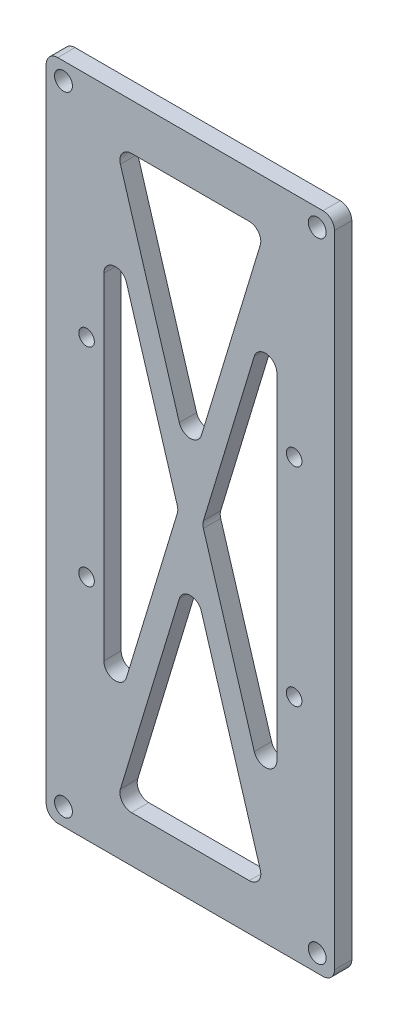
SolidWorks part; units mm, degrees
material "环氧玻璃布层压板"
ref_plane "前视基准面" through (0, 0, 0) normal (0, 0, 1) x (1, 0, 0)
ref_plane "上视基准面" through (0, 0, 0) normal (0, 1, 0) x (1, 0, 0)
ref_plane "右视基准面" through (0, 0, 0) normal (1, 0, 0) x (0, 0, -1)
sketch "草图1" plane through (0, 0, 0) normal (0, 0, 1) x (1, 0, 0)
  line L0 (25, -25) -> (25, 25)
  line L1 (-18, -18) -> (18, -18) construction
  line L2 (-18, -18) -> (-18, 18) construction
  line L3 (-18, 18) -> (18, 18) construction
  line L4 (18, -18) -> (18, 18) construction
  line L5 (0, 18) -> (0, -18) construction
  line L6 (-18, 0) -> (18, 0) construction
  line L7 (-25, 25) -> (25, 25)
  line L8 (-25, -25) -> (-25, 25)
  line L9 (-25, -25) -> (25, -25)
  circle A0 centre (18, 18) radius 1.35
  circle A1 centre (-18, 18) radius 1.35
  circle A2 centre (-18, -18) radius 1.35
  circle A3 centre (18, -18) radius 1.35
  point P0 (0, 0)
  dimension "D3" = 7
  dimension "D4" = 2.7
  dimension "D1" = 36
  dimension "D2" = 36
extrude "凸台-拉伸1" add sketch "草图1" along normal blind 3
sketch "草图2" plane through (0, 0, 3) normal (0, 0, 1) x (1, 0, 0)
  line L1 (-25, -57.5) -> (25, -57.5)
  line L2 (-25, -57.5) -> (-25, 57.5)
  line L3 (-25, 57.5) -> (25, 57.5)
  line L4 (25, -57.5) -> (25, 57.5)
  line L5 (0, 57.5) -> (0, -57.5) construction
  line L6 (-25, 0) -> (25, 0) construction
  line L8 (25, -25) -> (25, 25) construction
  line L9 (-22, -54.5) -> (22, -54.5) construction
  line L10 (-22, -54.5) -> (-22, 54.5) construction
  line L11 (-22, 54.5) -> (22, 54.5) construction
  line L12 (22, -54.5) -> (22, 54.5) construction
  line L13 (0, 54.5) -> (0, -54.5) construction
  line L14 (-22, 0) -> (22, 0) construction
  circle A0 centre (18, 18) radius 1.35 construction
  circle A1 centre (18, -18) radius 1.35 construction
  circle A2 centre (-18, -18) radius 1.35 construction
  circle A3 centre (-18, 18) radius 1.35 construction
  circle A4 centre (18, 18) radius 1.35
  circle A5 centre (18, -18) radius 1.35
  circle A6 centre (-18, -18) radius 1.35
  circle A7 centre (-18, 18) radius 1.35
  circle A8 centre (-22, 54.5) radius 1.55
  circle A9 centre (22, 54.5) radius 1.55
  circle A10 centre (-22, -54.5) radius 1.55
  circle A11 centre (22, -54.5) radius 1.55
  point P0 (0, 0)
  point P27 (0, 0)
  dimension "D5" = 3.1
  dimension "D2" = 115
  dimension "D3" = 3
  dimension "D4" = 3
extrude "凸台-拉伸2" add sketch "草图2" against normal blind 3
sketch "草图8" plane through (0, 0, 3) normal (0, 0, 1) x (1, 0, 0)
  line L5 (-25, -57.5) -> (25, -57.5) construction
  line L6 (-15, 49.5) -> (15, 49.5)
  line L15 (-15, 49.5) -> (-15, -49.5)
  line L16 (-15, -49.5) -> (15, -49.5)
  line L17 (15, 49.5) -> (15, -49.5)
  line L18 (-15, 49.5) -> (15, -49.5) construction
  line L19 (-15, -49.5) -> (15, 49.5) construction
  line L20 (25, -57.5) -> (25, 57.5) construction
  line L21 (-16.914, 48.92) -> (13.086, -50.08)
  line L22 (-13.086, -50.08) -> (16.914, 48.92)
  line L23 (-13.086, 50.08) -> (16.914, -48.92)
  line L24 (-16.914, -48.92) -> (13.086, 50.08)
  point P0 (0, 0)
  dimension "D1" = 8
  dimension "D2" = 10
  dimension "D3" = 2
  dimension "D4" = 2
extrude "切除-拉伸1" cut sketch "草图8" against normal through all contours L22 L16 L21 | L22 L23 L17 | L23 L24 L6 | L15 L24 L21
fillet "圆角2" radius 2 16 edges at (15, 42.6036, 1.5) (15, -42.6036, 1.5) (2.0898, 0, 1.5) (-2.0898, 0, 1.5) (-15, -42.6036, 1.5) (-15, 42.6036, 1.5) (25, 57.5, 1.5) (-25, 57.5, 1.5) (-25, -57.5, 1.5) (25, -57.5, 1.5) (0, -6.8964, 1.5) (12.9102, -49.5, 1.5) (-12.9102, -49.5, 1.5) (12.9102, 49.5, 1.5) (0, 6.8964, 1.5) (-12.9102, 49.5, 1.5)
